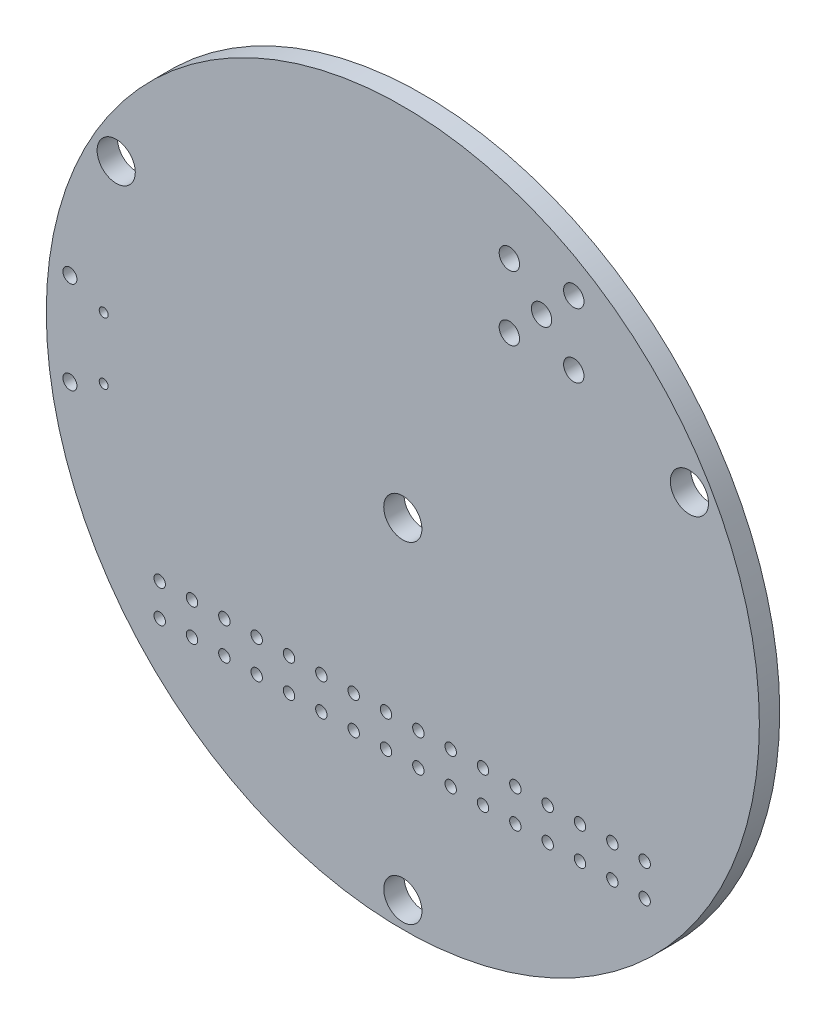
SolidWorks part; units mm, degrees
material "FR4"
ref_plane "Front Plane" through (0, 0, 0) normal (0, 0, 1) x (1, 0, 0)
ref_plane "Top Plane" through (0, 0, 0) normal (0, 1, 0) x (1, 0, 0)
ref_plane "Right Plane" through (0, 0, 0) normal (1, 0, 0) x (0, 0, -1)
ref_plane "Plane1" through (0, 0, 3.9726) normal (0, 0, 1) x (1, 0, 0)
sketch "Sketch1" plane through (0, 0, 3.9726) normal (0, 0, 1) x (1, 0, 0)
  circle A0 centre (43.43, 46.77) radius 0.8
  circle A1 centre (46.4599, 16.14) radius 0.45
  circle A2 centre (43.43, 51.83) radius 0.8
  circle A3 centre (43.9199, 16.14) radius 0.45
  circle A4 centre (48.9999, 16.14) radius 0.45
  circle A5 centre (41.3799, 16.14) radius 0.45
  circle A6 centre (38.37, 51.83) radius 0.8
  circle A7 centre (40.9, 49.3) radius 0.8
  circle A8 centre (38.37, 46.77) radius 0.8
  circle A9 centre (38.8399, 16.14) radius 0.45
  circle A10 centre (31.2199, 16.14) radius 0.45
  circle A11 centre (41.3799, 13.6) radius 0.45
  circle A12 centre (43.9199, 13.6) radius 0.45
  circle A13 centre (38.8399, 13.6) radius 0.45
  circle A14 centre (48.9999, 13.6) radius 0.45
  circle A15 centre (46.4599, 13.6) radius 0.45
  circle A16 centre (36.2999, 16.14) radius 0.45
  circle A17 centre (36.2999, 13.6) radius 0.45
  circle A18 centre (33.7599, 16.14) radius 0.45
  circle A19 centre (33.7599, 13.6) radius 0.45
  circle A20 centre (31.2199, 13.6) radius 0.45
  circle A21 centre (29.9999, 30) radius 1.5
  circle A22 centre (28.6799, 16.14) radius 0.45
  circle A23 centre (26.1399, 16.14) radius 0.45
  circle A24 centre (21.0599, 16.14) radius 0.45
  circle A25 centre (23.5999, 16.14) radius 0.45
  circle A26 centre (18.5199, 16.14) radius 0.45
  circle A27 centre (6.5, 32.225) radius 0.35
  circle A28 centre (6.5, 27.375) radius 0.35
  circle A29 centre (3.85, 33.425) radius 0.55
  circle A30 centre (10.8999, 16.14) radius 0.45
  circle A31 centre (3.85, 26.175) radius 0.55
  circle A32 centre (21.0599, 13.6) radius 0.45
  circle A33 centre (23.5999, 13.6) radius 0.45
  circle A34 centre (18.5199, 13.6) radius 0.45
  circle A35 centre (28.6799, 13.6) radius 0.45
  circle A36 centre (26.1399, 13.6) radius 0.45
  circle A37 centre (15.9799, 16.14) radius 0.45
  circle A38 centre (15.9799, 13.6) radius 0.45
  circle A39 centre (13.4399, 16.14) radius 0.45
  circle A40 centre (13.4399, 13.6) radius 0.45
  circle A41 centre (10.8999, 13.6) radius 0.45
  circle A42 centre (29.9999, 30) radius 28.011
  dimension "D1" = 56.022
extrude "Boss-Extrude1" add sketch "Sketch1" against normal blind 1.6
sketch "Sketch2" plane through (0, 0, 3.9726) normal (0, 0, 1) x (1, 0, 0)
  line L0 (3.85, 33.425) -> (3.85, 26.175)
  line L1 (6.5, 32.225) -> (6.5, 27.375)
  line L2 (3.85, 29.8) -> (6.5, 29.8)
ref_plane "Plane2" through (0, 29.8, 0) normal (0, 1, 0) x (1, 0, 0)
sketch "Sketch3" plane through (0, 0, 3.9726) normal (0, 0, 1) x (1, 0, 0)
  line L0 (29.9999, 30) -> (29.9999, 4) construction
  circle A0 centre (7.4833, 43) radius 1.5
  circle A1 centre (52.5166, 43) radius 1.5
  circle A2 centre (29.9999, 4) radius 1.5
  circle A3 centre (29.9999, 30) radius 26 construction
  circle A6 centre (29.9999, 30) radius 1.5 construction
  point P12 (29.9999, 30)
  dimension "D1" = 3
  dimension "D3" = 26
  dimension "D2" = 3
extrude "Cut-Extrude1" cut sketch "Sketch3" against normal up to next
